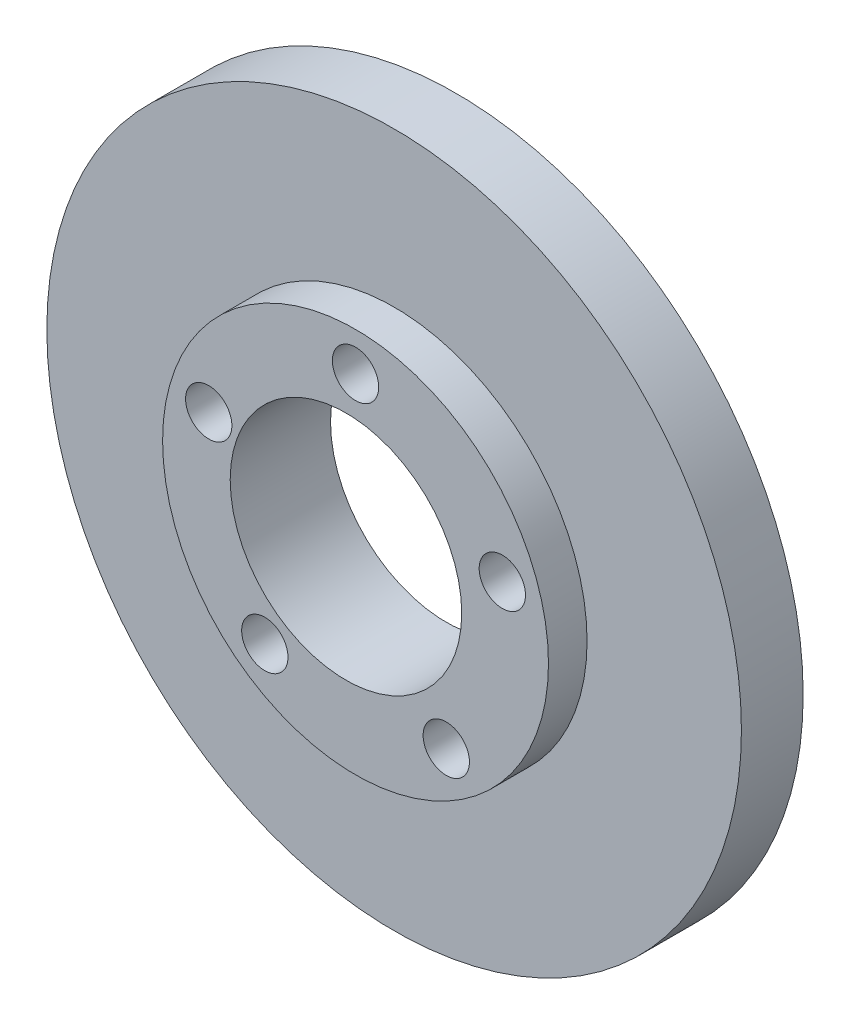
SolidWorks part; units mm, degrees
ref_plane "Front Plane" through (0, 0, 0) normal (0, 0, 1) x (1, 0, 0)
ref_plane "Top Plane" through (0, 0, 0) normal (0, 1, 0) x (1, 0, 0)
ref_plane "Right Plane" through (0, 0, 0) normal (1, 0, 0) x (0, 0, -1)
sketch "Sketch1" plane through (0, 0, 0) normal (0, 0, 1) x (1, 0, 0)
  circle A0 centre (0, 0) radius 90
  circle A1 centre (-2.4818, 0) radius 30
  dimension "D1" = 180
  dimension "D2" = 60
extrude "Boss-Extrude1" add sketch "Sketch1" along normal mid plane 16
sketch "Sketch2" plane through (0, 0, 8) normal (0, 0, 1) x (1, 0, 0)
  circle A0 centre (0, 0) radius 50
  circle A1 centre (-2.4818, 0) radius 30 construction
  circle A2 centre (-2.4818, 0) radius 30
  dimension "D1" = 100
extrude "Boss-Extrude2" add sketch "Sketch2" along normal blind 10
sketch "Sketch3" plane through (0, 0, 18) normal (0, 0, 1) x (1, 0, 0)
  circle A0 centre (0, 0) radius 40 construction
  point P3 (0, 40)
  point P4 (38.0423, 12.3607)
  point P7 (23.5114, -32.3607)
  point P8 (-23.5114, -32.3607)
  point P9 (-38.0423, 12.3607)
  point P10 (0, 0)
  dimension "D1" = 5
hole_wizard "Ø12.0 (12) Diameter Hole1" positions "3DSketch1" profile "Sketch4" hole size "Ø12.0" standard "ISO" end condition through all
sketch3d "3DSketch1"
  point P0 (0, 40, 18)
  point P3 (-38.0423, 12.3607, 18)
  point P6 (-23.5114, -32.3607, 18)
  point P9 (23.5114, -32.3607, 18)
  point P12 (38.0423, 12.3607, 18)
sketch "Sketch4" plane through (0, 40, 18) normal (1, 0, 0) x (0, -1, 0)
  line L0 (0, 0) -> (0, 26)
  line L1 (0, 26) -> (6, 26)
  line L2 (6, 26) -> (6, 0)
  line L5 (6, 0) -> (0, 0)
  line L11 (0, -6.35) -> (0, 107.95) construction
  dimension "Thru Hole Dia." = 12
  dimension "Thru Hole Depth" = 26
